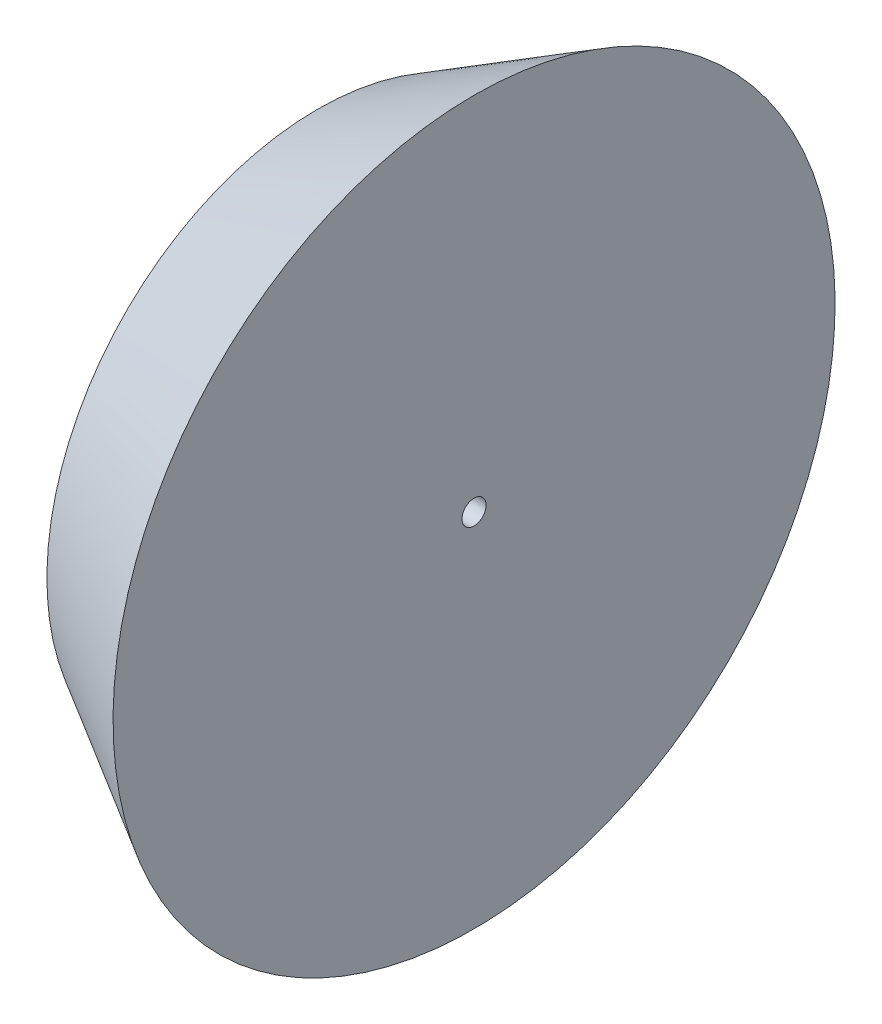
SolidWorks part; units mm, degrees
ref_plane "Front Plane" through (0, 0, 0) normal (0, 0, 1) x (1, 0, 0)
ref_plane "Top Plane" through (0, 0, 0) normal (0, 1, 0) x (1, 0, 0)
ref_plane "Right Plane" through (0, 0, 0) normal (1, 0, 0) x (0, 0, -1)
sketch "Sketch2" plane through (0, 0, 0) normal (0, 0, 1) x (1, 0, 0)
  line L0 (0, 0) -> (0, 142.8397)
  line L1 (0, 142.8397) -> (82.55, 190.5)
  line L2 (82.55, 190.5) -> (82.55, 0)
  line L3 (82.55, 190.5) -> (0, 190.5) construction
  line L4 (0, 190.5) -> (0, 142.8397) construction
  line L5 (82.55, 0) -> (0, 0)
  dimension "D1" = 82.55
  dimension "D2" = 30
  dimension "D3" = 190.5
revolve "Revolve1" add sketch "Sketch2" angle 360 about L5
ref_plane "Plane1" through (0, 0, 0) normal (-1, 0, 0) x (0, 0, 1)
sketch "Sketch3" plane through (0, 0, 0) normal (-1, 0, 0) x (0, 0, 1)
  circle A0 centre (0, 0) radius 6.35
  dimension "D1" = 12.7
extrude "Cut-Extrude1" cut sketch "Sketch3" against normal up to surface (82.55 mm away) up to face at (82.55, 190.5, 0)
